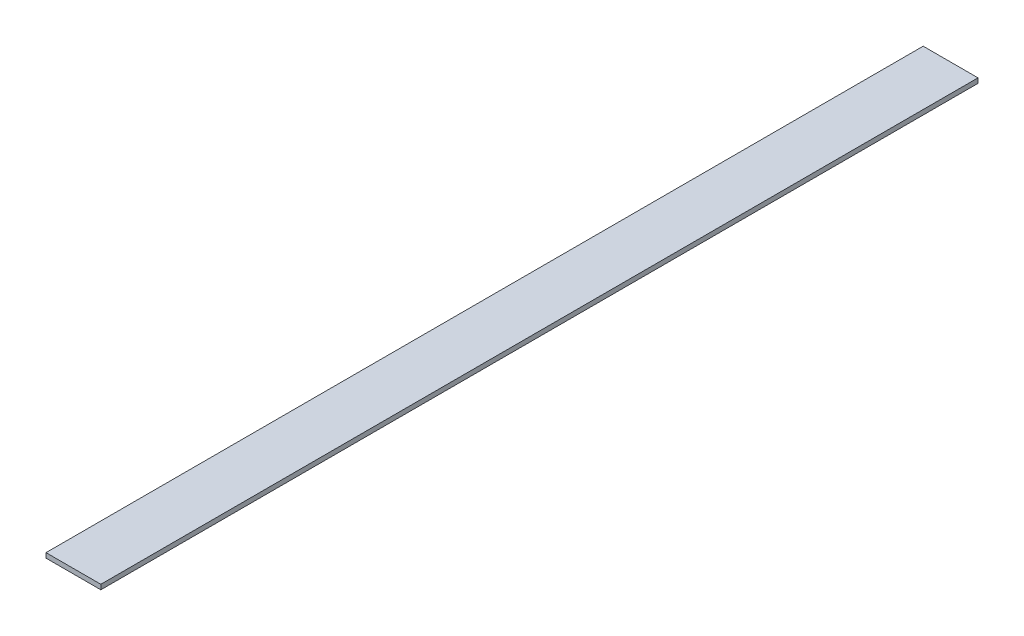
SolidWorks part; units mm, degrees
ref_plane "Front Plane" through (0, 0, 0) normal (0, 0, 1) x (1, 0, 0)
ref_plane "Top Plane" through (0, 0, 0) normal (0, 1, 0) x (1, 0, 0)
ref_plane "Right Plane" through (0, 0, 0) normal (1, 0, 0) x (0, 0, -1)
sketch "Outline" plane through (0, 0, 0) normal (0, 1, 0) x (1, 0, 0)
  line L0 (0, 0) -> (57.15, 0)
  line L1 (57.15, 0) -> (57.15, -914.4)
  line L2 (57.15, -914.4) -> (0, -914.4)
  line L3 (0, -914.4) -> (0, 0)
  dimension "D1" = 914.4
  dimension "D2" = 57.15
sketch "Nose Gear Hole" plane through (0, 0, 0) normal (0, 1, 0) x (1, 0, 0)
  line L0 (0, 0) -> (0, -127) construction
  line L1 (0, -914.4) -> (0, 0) construction
  line L2 (0, -127) -> (25.4, -127) construction
  circle A0 centre (25.4, -127) radius 6
  dimension "D3" = 12
  dimension "D1" = 127
  dimension "D2" = 25.4
extrude "Boss-Extrude1" add sketch "Outline" along normal blind 5 contours L3 L0 L1 L2
